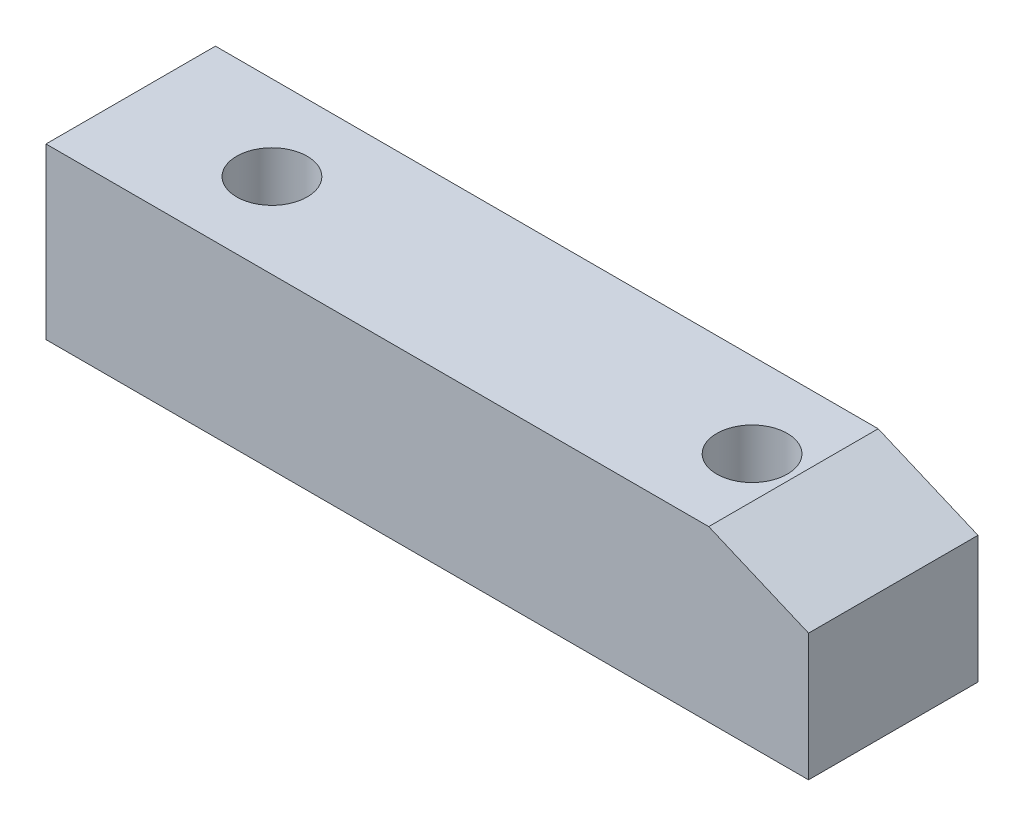
SolidWorks part; units mm, degrees
ref_plane "Plan de face" through (0, 0, 0) normal (0, 0, 1) x (1, 0, 0)
ref_plane "Plan de dessus" through (0, 0, 0) normal (0, 1, 0) x (1, 0, 0)
ref_plane "Plan de droite" through (0, 0, 0) normal (1, 0, 0) x (0, 0, -1)
sketch "Esquisse1" plane through (0, 0, 0) normal (0, 0, 1) x (1, 0, 0)
  line L1 (0, 0) -> (27, 0)
  line L2 (0, 0) -> (0, -6)
  line L3 (0, -6) -> (27, -6)
  line L4 (27, 0) -> (27, -6)
  dimension "D1" = 27
  dimension "D2" = 6
extrude "Boss.-Extru.1" add sketch "Esquisse1" along normal blind 6
sketch "Esquisse2" plane through (0, 0, 0) normal (0, 1, 0) x (1, 0, 0)
  line L0 (0, -6) -> (0, 0) construction
  line L1 (27, -6) -> (27, 0) construction
  circle A0 centre (22, -3) radius 1.2285
  circle A1 centre (5, -3) radius 1.2285
  dimension "D1" = 5
  dimension "D2" = 5
hole_wizard "Trou taraudé M31" positions "Esquisse3D1" profile "Esquisse3" tap size "M3" standard "ISO"
sketch3d "Esquisse3D1"
  point P0 (5, 0, 3)
  point P3 (22, 0, 3)
sketch "Esquisse3" plane through (5, 0, 3) normal (1, 0, 0) x (0, 0, 1)
  line L0 (0, 0) -> (0, 9.2511)
  line L1 (0, 9.2511) -> (1.25, 8.5)
  line L2 (1.25, 8.5) -> (1.25, 0)
  line L5 (1.25, 0) -> (0, 0)
  line L10 (0, 9.2511) -> (-1.25, 8.5) construction
  line L11 (0, -6.35) -> (0, 107.95) construction
  dimension "Diamètre du trou pour taraudage" = 2.5
  dimension "Profondeur du trou pour taraudage" = 8.5
  dimension "Angle de pointe" = 118
cosmetic thread "Filetage de perçage1" parameters "D1"=6, "D2"=3
cosmetic thread "Filetage de perçage2" parameters "D1"=6, "D2"=3
chamfer "Chanfrein1" distance 1.5 angle 67 1 edges at (27, 0, 3)
